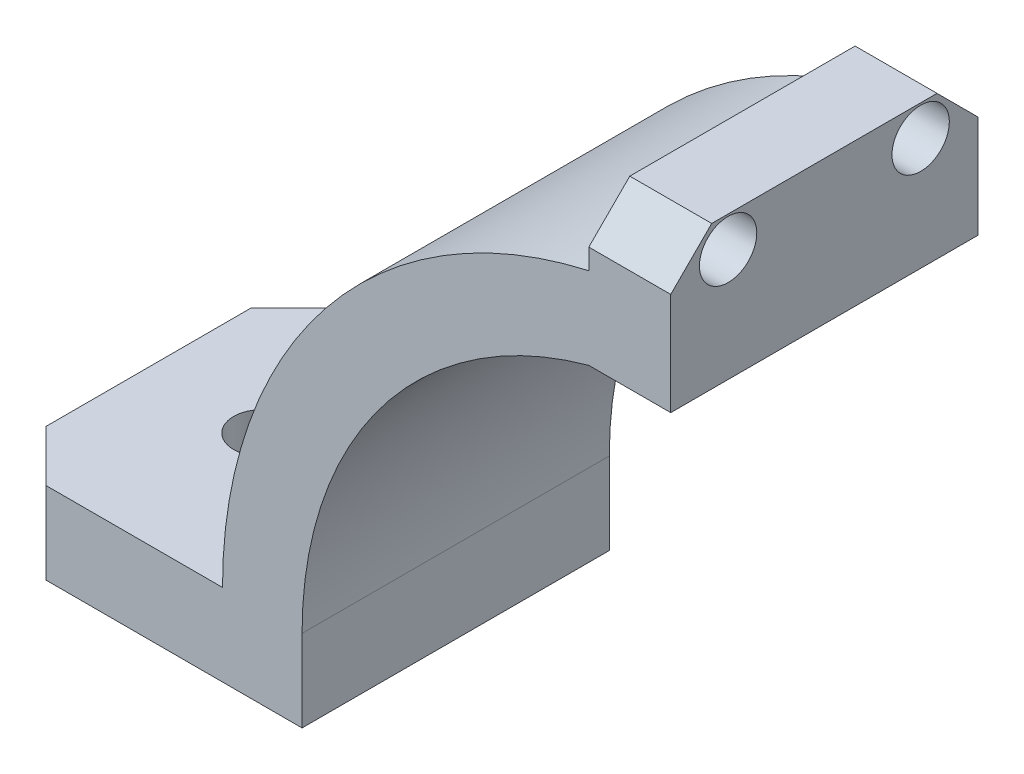
SolidWorks part; units mm, degrees
ref_plane "Front Plane" through (0, 0, 0) normal (0, 0, 1) x (1, 0, 0)
ref_plane "Top Plane" through (0, 0, 0) normal (0, 1, 0) x (1, 0, 0)
ref_plane "Right Plane" through (0, 0, 0) normal (1, 0, 0) x (0, 0, -1)
sketch "Sketch1" plane through (0, 0, 0) normal (0, 0, 1) x (1, 0, 0)
  line L0 (0, 0) -> (0, 50000) construction
  line L2 (-19, 0) -> (-19, -4)
  line L3 (-19, -4) -> (-34, -4)
  line L4 (-34, -4) -> (-34, 0)
  line L5 (-34, 0) -> (-22.8832, 0)
  line L6 (-5, 22.3303) -> (-5, 25.3303)
  line L7 (-5, 25.3303) -> (-1, 25.3303)
  line L8 (-1, 25.3303) -> (-1, 18.3303)
  line L9 (-1, 18.3303) -> (-5, 18.3303)
  arc A0 (-19, 0) -> (-5, 18.3303) centre (0, 0) cw
  arc A1 (-22.8832, 0) -> (-5, 22.3303) centre (0, 0) cw
  dimension "D2" = 19
  dimension "D1" = 4
  dimension "D3" = 15
  dimension "D4" = 4
  dimension "D5" = 4
  dimension "D6" = 7
  dimension "D7" = 1
extrude "Boss-Extrude1" add sketch "Sketch1" along normal blind 15
chamfer "Chamfer1" distance 2.5 2 edges at (-34, -2, 0) (-34, -2, 15)
sketch "Sketch2" plane through (-5, 0, 0) normal (-1, 0, 0) x (0, 0, 1)
  line L0 (15, 25.3303) -> (15, 22.3303) construction
  line L1 (0, 25.3303) -> (0, 22.3303) construction
  circle A0 centre (2.8, 23.8303) radius 1.4
  circle A1 centre (12.2, 23.8303) radius 1.4
  point P8 (0, 23.8303)
  dimension "D1" = 2.8
  dimension "D2" = 2.8
  dimension "D3" = 2.8
extrude "Cut-Extrude1" cut sketch "Sketch2" against normal blind 15
chamfer "Chamfer2" distance 2 angle 45 2 edges at (-3, 25.3303, 15) (-3, 25.3303, 0)
sketch "Sketch3" plane through (0, 0, 0) normal (0, 1, 0) x (1, 0, 0)
  line L0 (-34, -12.5) -> (-34, -2.5) construction
  line L2 (-22.8832, 0) -> (-34, 0.1) construction
  line L3 (45.4373, 0.1) -> (-44.4791, 0.1) construction
  circle A0 centre (-28.4416, -7.5) radius 1.4
  point P2 (-28.4416, 0.05)
  point P5 (-34, -7.5)
  dimension "D1" = 2.8
extrude "Cut-Extrude2" cut sketch "Sketch3" against normal through all contours A0
